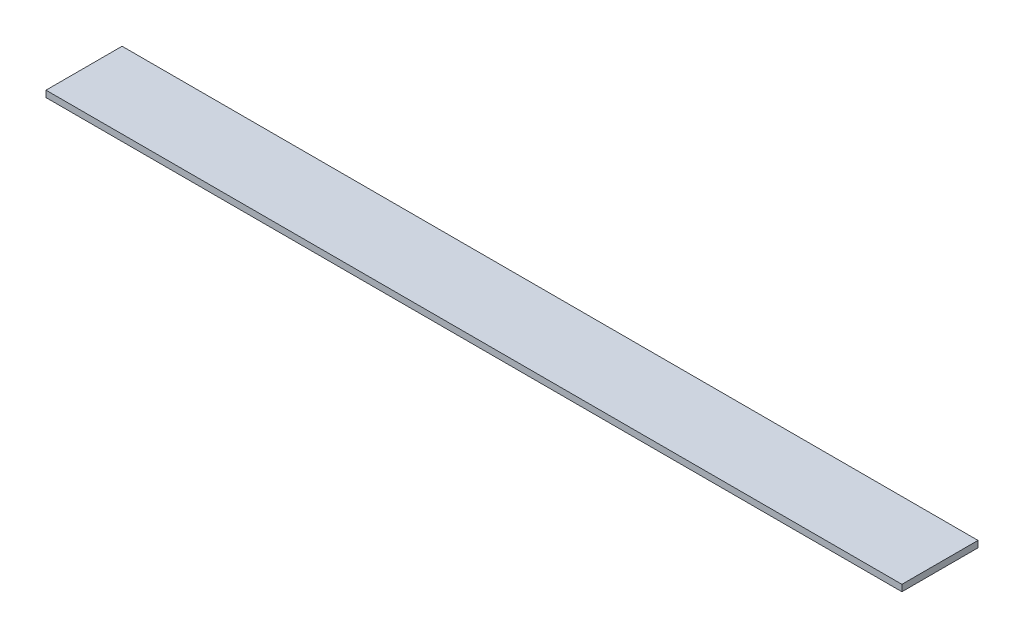
SolidWorks part; units mm, degrees
ref_plane "Front Plane" through (0, 0, 0) normal (0, 0, 1) x (1, 0, 0)
ref_plane "Top Plane" through (0, 0, 0) normal (0, 1, 0) x (1, 0, 0)
ref_plane "Right Plane" through (0, 0, 0) normal (1, 0, 0) x (0, 0, -1)
sketch "Sketch1" plane through (0, 0, 0) normal (0, 1, 0) x (1, 0, 0)
  line L1 (-112.5, 10) -> (112.5, 10)
  line L2 (-112.5, 10) -> (-112.5, -10)
  line L3 (-112.5, -10) -> (112.5, -10)
  line L4 (112.5, 10) -> (112.5, -10)
  line L5 (-112.5, 10) -> (112.5, -10) construction
  line L6 (-112.5, -10) -> (112.5, 10) construction
  point P0 (0, 0)
  dimension "D1" = 225
  dimension "D2" = 20
extrude "Boss-Extrude1" add sketch "Sketch1" along normal blind 1.7
